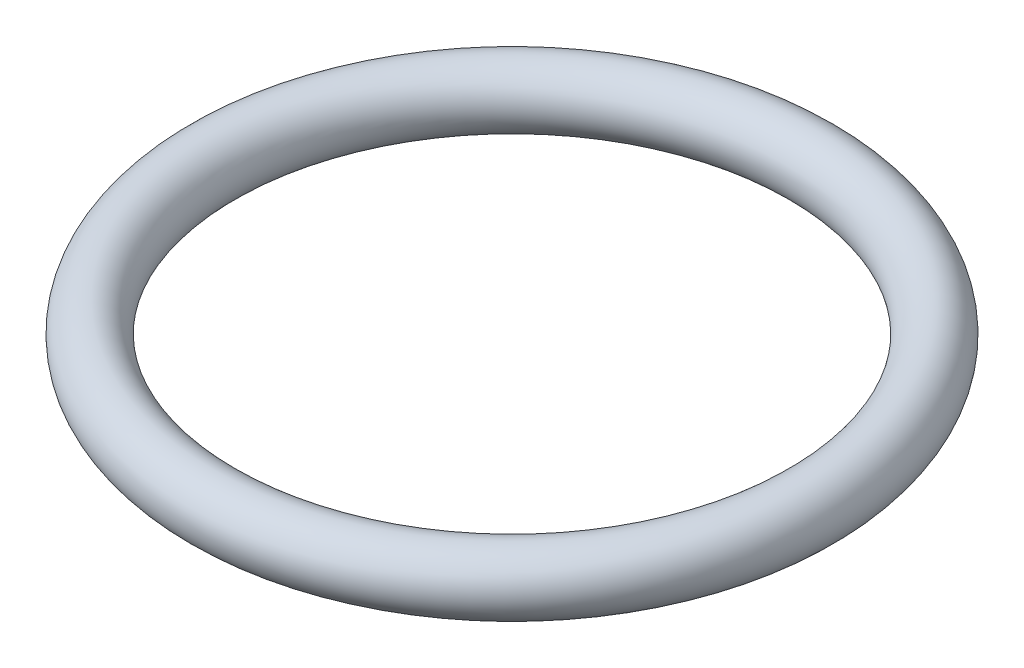
SolidWorks part; units mm, degrees
material "Silicon Rubber"
ref_plane "Front Plane" through (0, 0, 0) normal (0, 0, 1) x (1, 0, 0)
ref_plane "Top Plane" through (0, 0, 0) normal (0, 1, 0) x (1, 0, 0)
ref_plane "Right Plane" through (0, 0, 0) normal (1, 0, 0) x (0, 0, -1)
sketch "Sketch2" plane through (0, 0, 0) normal (0, 0, 1) x (1, 0, 0)
  line L0 (0, 0) -> (8.61, 0) construction
  circle A0 centre (0, 0) radius 0.89
  dimension "D1" = 1.78
  dimension "D2" = 8.61
sketch "Sketch3" plane through (0, 0, 0) normal (0, 0, 1) x (1, 0, 0)
  line L0 (8.61, 0) -> (8.61, 6.1646) construction
revolve "Revolve3" add sketch "Sketch2" angle 360 about L0
